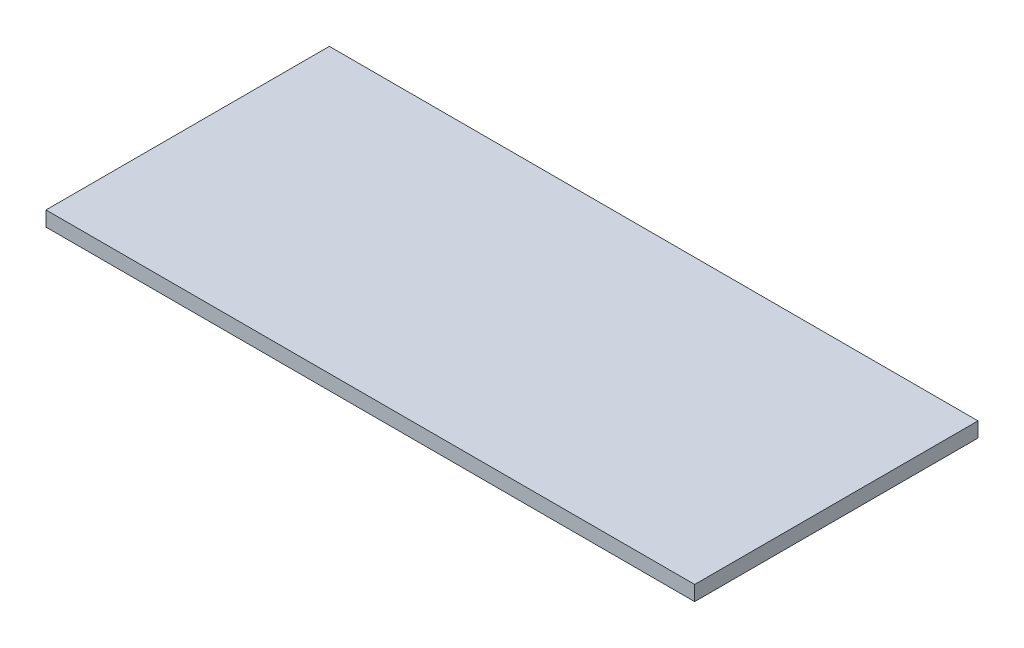
SolidWorks part; units mm, degrees
ref_plane "前视基准面" through (0, 0, 0) normal (0, 0, 1) x (1, 0, 0)
ref_plane "上视基准面" through (0, 0, 0) normal (0, 1, 0) x (1, 0, 0)
ref_plane "右视基准面" through (0, 0, 0) normal (1, 0, 0) x (0, 0, -1)
sketch "草图1" plane through (0, 0, 0) normal (0, 1, 0) x (1, 0, 0)
  line L1 (0, 0) -> (870, 0)
  line L2 (0, 0) -> (0, 380)
  line L3 (0, 380) -> (870, 380)
  line L4 (870, 0) -> (870, 380)
  dimension "D1" = 870
  dimension "D2" = 380
extrude "凸台-拉伸1" add sketch "草图1" along normal blind 20
